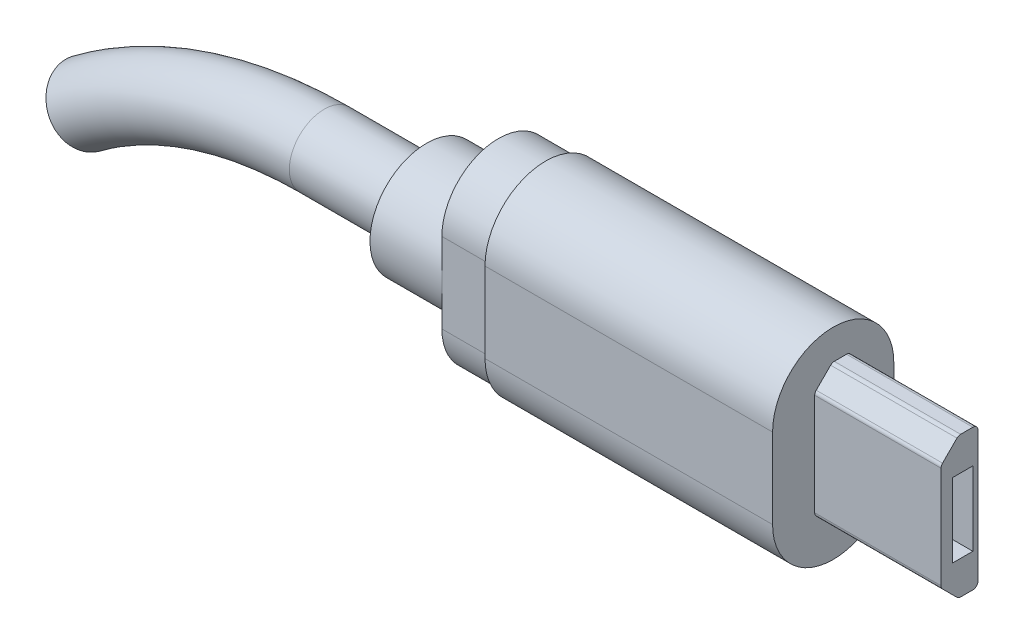
SolidWorks part; units mm, degrees
ref_plane "Front" through (0, 0, 0) normal (0, 0, 1) x (1, 0, 0)
ref_plane "Top" through (0, 0, 0) normal (0, 1, 0) x (1, 0, 0)
ref_plane "Right" through (0, 0, 0) normal (1, 0, 0) x (0, 0, -1)
sketch "Эскиз1" plane through (0, 0, 0) normal (1, 0, 0) x (0, 0, -1)
  line L0 (0, -1.95) -> (0, 1.95) construction
  line L1 (-2.95, -1.95) -> (-2.95, 1.95)
  line L2 (2.95, -1.95) -> (2.95, 1.95)
  arc A0 (-2.95, -1.95) -> (2.95, -1.95) centre (0, -1.95) ccw
  arc A1 (2.95, 1.95) -> (-2.95, 1.95) centre (0, 1.95) ccw
  point P2 (0, 0)
  point P8 (0, -4.9)
  point P9 (0, 4.9)
  dimension "D1" = 5.9
  dimension "D2" = 9.8
extrude "Бобышка-Вытянуть1" add sketch "Эскиз1" against normal blind 14
sketch "Эскиз3" plane through (-14, 0, 0) normal (-1, 0, 0) x (0, 0, 1)
  line L0 (0, 1.95) -> (0, -1.95) construction
  line L1 (2.75, 1.95) -> (2.75, -1.95)
  line L2 (-2.75, 1.95) -> (-2.75, -1.95)
  arc A0 (2.75, 1.95) -> (-2.75, 1.95) centre (0, 1.95) ccw
  arc A1 (-2.75, -1.95) -> (2.75, -1.95) centre (0, -1.95) ccw
  arc A2 (-2.95, -1.95) -> (2.95, -1.95) centre (0, -1.95) ccw construction
  point P2 (0, 0)
  dimension "D1" = 5.5
extrude "Бобышка-Вытянуть2" add sketch "Эскиз3" along normal offset from surface (2.3 mm away) 16.3 up to face at (0, 0, 0)
sketch "Эскиз4" plane through (-16.3, 0, 0) normal (-1, 0, 0) x (0, 0, 1)
  line L0 (-2.75, -1.95) -> (-2.75, 1.95) construction
  circle A0 centre (0, 0) radius 2.75
extrude "Бобышка-Вытянуть3" add sketch "Эскиз4" along normal blind 3.5
sketch "Эскиз5" plane through (-19.8, 0, 0) normal (-1, 0, 0) x (0, 0, 1)
  circle A0 centre (0, 0) radius 1.7
  dimension "D1" = 3.4
sketch "Эскиз6" plane through (0, 0, 0) normal (0, 0, 1) x (1, 0, 0)
  line L0 (-19.8, 0) -> (-24.7762, 0)
  line L1 (-19.8, 1.7) -> (-19.8, -1.7) construction
  arc A0 (-24.7762, 0) -> (-36.3422, -3.8456) centre (-24.7762, -19.3158) ccw
sweep "По траектории1" add profiles "Эскиз5" path "Эскиз6"
sketch "Эскиз7" plane through (0, 0, 0) normal (1, 0, 0) x (0, 0, -1)
  line L0 (-0.05, -3.43) -> (-0.9, -2.58)
  line L1 (-0.9, -2.58) -> (-0.9, 2.58)
  line L2 (-0.05, -3.43) -> (0.9, -3.43)
  line L3 (0.9, -3.43) -> (0.9, 3.43)
  line L4 (-0.05, 3.43) -> (0.9, 3.43)
  line L5 (-0.9, -3.43) -> (0.9, 3.43) construction
  line L6 (0.9, -3.43) -> (-0.9, 3.43) construction
  line L7 (-0.9, 2.58) -> (-0.05, 3.43)
  point P0 (0, 0)
  dimension "D1" = 6.86
  dimension "D2" = 1.8
extrude "Бобышка-Вытянуть4" add sketch "Эскиз7" along normal blind 6.15
fillet "Скругление1" radius 0.25 6 edges at (3.075, -3.43, -0.9) (3.075, 3.43, -0.9) (3.075, 3.43, 0.05) (3.075, 2.58, 0.9) (3.075, -3.43, 0.05) (3.075, -2.58, 0.9)
sketch "Эскиз8" plane through (6.15, 0, 0) normal (1, 0, 0) x (0, 0, -1)
  line L1 (0.65, -1.8) -> (-0.35, -1.8)
  line L2 (0.65, -1.8) -> (0.65, 1.8)
  line L3 (0.65, 1.8) -> (-0.35, 1.8)
  line L4 (-0.35, -1.8) -> (-0.35, 1.8)
  line L5 (0.65, -1.8) -> (-0.35, 1.8) construction
  line L6 (0.65, 1.8) -> (-0.35, -1.8) construction
  line L7 (0.9, -3.18) -> (0.9, 3.18) construction
  point P4 (0.15, 0)
  point P7 (0, 0)
  point P9 (0, 0)
  dimension "D1" = 3.6
  dimension "D2" = 1
  dimension "D3" = 0.25
extrude "Вырез-Вытянуть1" cut sketch "Эскиз8" against normal blind 2.75
